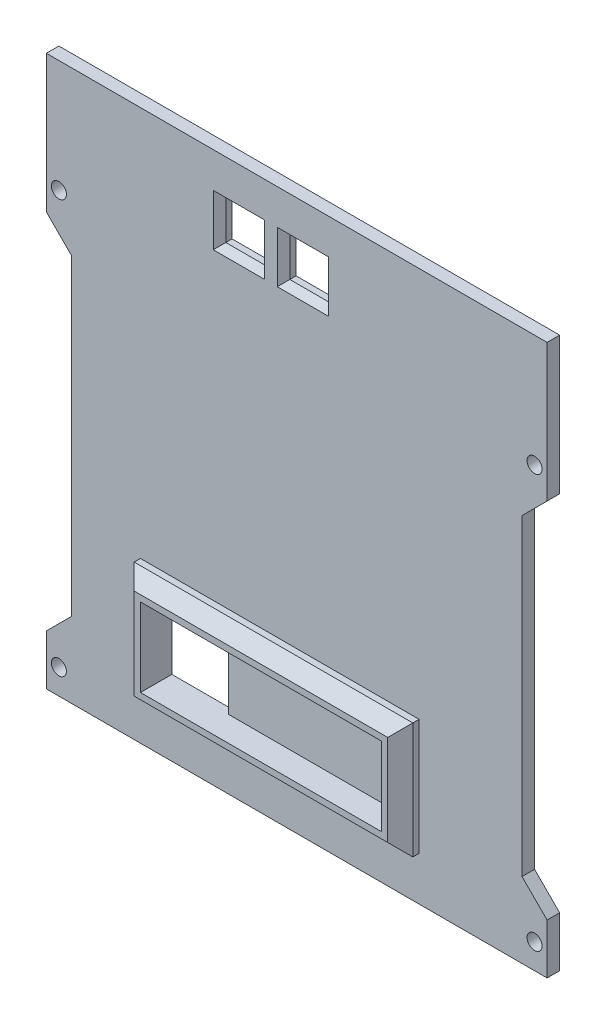
SolidWorks part; units mm, degrees
ref_plane "前视基准面" through (0, 0, 0) normal (0, 0, 1) x (1, 0, 0)
ref_plane "上视基准面" through (0, 0, 0) normal (0, 1, 0) x (1, 0, 0)
ref_plane "右视基准面" through (0, 0, 0) normal (1, 0, 0) x (0, 0, -1)
other "Configuration Table"
sketch "草图1" plane through (0, 0, 0) normal (0, 0, 1) x (1, 0, 0)
  line L0 (-68.63, 24.2) -> (-68.63, 24.3)
  line L1 (11.17, 24.2) -> (11.17, 24.3)
  line L2 (5.17, 38.1) -> (-62.63, 38.1)
  line L3 (-35.03, 25.48) -> (-40.83, 25.48) construction
  line L4 (-68.63, 24.3) -> (-62.63, 24.3)
  line L5 (-62.63, 24.3) -> (-62.63, 38.1)
  line L6 (-62.63, 38.1) -> (-68.63, 38.1)
  line L7 (-68.63, 38.1) -> (-68.63, 24.3)
  line L10 (-62.63, 38.1) -> (-68.63, 38.1)
  line L11 (-68.63, 38.1) -> (-68.63, 24.3)
  line L12 (5.17, 24.3) -> (11.17, 24.3)
  line L13 (11.17, 24.3) -> (11.17, 38.1)
  line L14 (11.17, 38.1) -> (5.17, 38.1)
  line L15 (5.17, 38.1) -> (5.17, 24.3)
  line L16 (5.17, 24.2) -> (5.17, -47.62)
  line L17 (5.17, -47.62) -> (-62.63, -47.62)
  line L18 (-62.63, -47.62) -> (-62.63, 24.2)
  line L19 (-62.63, 24.2) -> (-68.63, 24.2)
  line L20 (-68.63, 24.2) -> (-68.63, 16.2)
  line L21 (-68.63, 16.2) -> (-64.63, 12.2)
  line L22 (-64.63, 12.2) -> (-64.63, -37.62)
  line L23 (-64.63, -37.62) -> (-68.63, -41.62)
  line L24 (-68.63, -41.62) -> (-68.63, -49.62)
  line L25 (-68.63, -49.62) -> (11.17, -49.62)
  line L26 (11.17, -49.62) -> (11.17, -41.62)
  line L27 (11.17, -41.62) -> (7.17, -37.62)
  line L28 (7.17, -37.62) -> (7.17, 12.2)
  line L29 (7.17, 12.2) -> (11.17, 16.2)
  line L30 (11.17, 16.2) -> (11.17, 24.2)
  line L31 (11.17, 24.2) -> (5.17, 24.2)
  line L36 (-68.63, 24.2) -> (-68.63, 16.2)
  line L37 (-68.63, 16.2) -> (-64.63, 12.2)
  line L38 (-64.63, 12.2) -> (-64.63, -37.62)
  line L39 (-64.63, -37.62) -> (-68.63, -41.62)
  line L40 (-68.63, -41.62) -> (-68.63, -49.62)
  line L41 (-68.63, -49.62) -> (11.17, -49.62)
  line L42 (11.17, -49.62) -> (11.17, -41.62)
  line L43 (11.17, -41.62) -> (7.17, -37.62)
  line L44 (7.17, -37.62) -> (7.17, 12.2)
  line L45 (7.17, 12.2) -> (11.17, 16.2)
  line L46 (11.17, 16.2) -> (11.17, 24.2)
  line L49 (11.17, 24.3) -> (11.17, 38.1)
  line L50 (11.17, 38.1) -> (5.17, 38.1)
  line L52 (-35.03, 25.48) -> (-40.83, 25.48)
  line L53 (-35.03, 31.28) -> (-35.03, 25.48) construction
  line L54 (-35.03, 31.28) -> (-35.03, 25.48)
  line L55 (-24.83, 31.28) -> (-24.83, 25.48) construction
  line L56 (-24.83, 31.28) -> (-24.83, 25.48)
  line L57 (-24.83, 25.48) -> (-30.63, 25.48) construction
  line L58 (-24.83, 25.48) -> (-30.63, 25.48)
  line L59 (-34.83, 31.28) -> (-34.83, 25.48)
  line L60 (-40.83, 25.48) -> (-35.03, 25.48)
  line L61 (-40.83, 25.48) -> (-40.83, 31.28)
  line L62 (-40.83, 31.28) -> (-35.03, 31.28)
  line L63 (-35.03, 25.48) -> (-35.03, 31.28)
  line L64 (-30.63, 25.48) -> (-24.83, 25.48)
  line L65 (-30.63, 25.48) -> (-30.63, 31.28)
  line L66 (-30.63, 31.28) -> (-24.83, 31.28)
  line L67 (-24.83, 25.48) -> (-24.83, 31.28)
  line L68 (-35.03, 25.28) -> (-40.83, 25.28)
  line L69 (-41.03, 25.48) -> (-41.03, 31.48)
  line L70 (-41.03, 31.48) -> (-35.03, 31.48)
  line L71 (-41.03, 25.48) -> (-41.03, 25.28)
  line L72 (-41.03, 25.28) -> (-40.83, 25.28)
  line L73 (-30.83, 25.48) -> (-30.83, 31.48)
  line L74 (-41.03, 25.28) -> (-34.83, 25.28)
  line L75 (-41.03, 25.28) -> (-41.03, 31.48)
  line L76 (-41.03, 31.48) -> (-34.83, 31.48)
  line L77 (-34.83, 25.28) -> (-34.83, 31.48)
  line L78 (-30.83, 31.48) -> (-24.83, 31.48)
  line L79 (-24.63, 31.28) -> (-24.63, 25.48)
  line L81 (-30.83, 31.48) -> (-24.63, 31.48)
  line L82 (-30.83, 31.48) -> (-30.83, 25.28)
  line L83 (-30.83, 25.28) -> (-24.63, 25.28)
  line L84 (-24.63, 31.48) -> (-24.63, 25.28)
  circle A0 centre (-66.63, -45.62) radius 1.2 construction
  circle A1 centre (-66.63, -45.62) radius 1.2
  circle A2 centre (-66.63, 20.2) radius 1.2 construction
  circle A3 centre (-66.63, 20.2) radius 1.2
  circle A4 centre (9.17, 20.2) radius 1.2 construction
  circle A5 centre (9.17, 20.2) radius 1.2
  circle A6 centre (9.17, -45.62) radius 1.2 construction
  circle A7 centre (9.17, -45.62) radius 1.2
  dimension "D1" = 0
  dimension "D2" = 0
  dimension "D3" = 0
  dimension "D4" = 0.2
  dimension "D5" = 0.2
  dimension "D6" = 0.2
extrude "凸台-拉伸1" add sketch "草图1" along normal blind 2 contours L49 L50 L2 L10 L11 L0 L36 L37 L38 L39 L40 L41 L42 L43 L44 L45 L46 L1 A7 A5 A3 A1 L77 L74 L68 L72 L71 L69 L70 L76 L59 L81 L84 L79 L83 L82 L73 L78
sketch "草图2" plane through (0, 0, 2) normal (0, 0, 1) x (1, 0, 0)
  line L0 (-58.03, -22.82) -> (-39.83, -22.82) construction
  line L1 (-50.63, -27.12) -> (-12.23, -27.12)
  line L2 (-50.63, -27.12) -> (-50.63, -39.62)
  line L3 (-50.63, -39.62) -> (-12.23, -39.62)
  line L4 (-12.23, -27.12) -> (-12.23, -39.62)
  line L5 (-58.03, -22.82) -> (-39.83, -22.82)
  line L6 (-39.83, -22.82) -> (-39.83, -35.02) construction
  line L7 (-39.83, -22.82) -> (-39.83, -35.02)
  line L8 (-39.83, -35.02) -> (-39.83, -47.62) construction
  line L9 (-39.83, -35.02) -> (-39.83, -47.62)
  line L10 (-50.63, -27.12) -> (-64.63, -27.12)
  line L11 (-50.63, -39.62) -> (-50.63, -49.62)
  line L12 (11.17, 16.2) -> (11.17, 38.1)
  line L13 (11.17, 38.1) -> (-68.63, 38.1)
  line L14 (-68.63, 38.1) -> (-68.63, 16.2)
  line L15 (-68.63, 16.2) -> (-64.63, 12.2)
  line L16 (-64.63, 12.2) -> (-64.63, -37.62)
  line L17 (-64.63, -37.62) -> (-68.63, -41.62)
  line L18 (-68.63, -41.62) -> (-68.63, -49.62)
  line L19 (-68.63, -49.62) -> (11.17, -49.62)
  line L20 (11.17, -49.62) -> (11.17, -41.62)
  line L21 (11.17, -41.62) -> (7.17, -37.62)
  line L22 (7.17, -37.62) -> (7.17, 12.2)
  line L23 (7.17, 12.2) -> (11.17, 16.2)
  line L24 (11.17, 16.2) -> (11.17, 38.1)
  line L25 (11.17, 38.1) -> (-68.63, 38.1)
  line L26 (-68.63, 38.1) -> (-68.63, 16.2)
  line L27 (-68.63, 16.2) -> (-64.63, 12.2)
  line L28 (-64.63, 12.2) -> (-64.63, -37.62)
  line L29 (-64.63, -37.62) -> (-68.63, -41.62)
  line L30 (-68.63, -41.62) -> (-68.63, -49.62)
  line L31 (-68.63, -49.62) -> (11.17, -49.62)
  line L32 (11.17, -49.62) -> (11.17, -41.62)
  line L33 (11.17, -41.62) -> (7.17, -37.62)
  line L34 (7.17, -37.62) -> (7.17, 12.2)
  line L35 (7.17, 12.2) -> (11.17, 16.2)
  dimension "D2" = 38.4
  dimension "D3" = 12.5
  dimension "D4" = 14
  dimension "D5" = 10
  dimension "D1" = 0
extrude "切除-拉伸1" cut sketch "草图2" against normal blind 1 contours L7 L9 L3 L4 L1 | L9 L7 L1 L2 L3
sketch "草图3" plane through (0, 0, 1) normal (0, 0, 1) x (1, 0, 0)
  line L1 (-50.63, -27.12) -> (-40.63, -27.12)
  line L2 (-50.63, -27.12) -> (-50.63, -39.62)
  line L3 (-50.63, -39.62) -> (-40.63, -39.62)
  line L4 (-12.23, -27.12) -> (-50.63, -27.12)
  line L5 (-50.63, -27.12) -> (-50.63, -39.62)
  line L6 (-50.63, -39.62) -> (-12.23, -39.62)
  line L7 (-12.23, -39.62) -> (-12.23, -27.12)
  line L8 (-12.23, -27.12) -> (-50.63, -27.12)
  line L9 (-50.63, -27.12) -> (-50.63, -39.62)
  line L10 (-50.63, -39.62) -> (-12.23, -39.62)
  line L11 (-12.23, -39.62) -> (-12.23, -27.12)
  line L12 (-40.63, -27.12) -> (-40.63, -39.62)
  line M6 (-12.23, -27.12) -> (-50.63, -27.12)
  line M7 (-50.63, -27.12) -> (-50.63, -39.62)
  line M8 (-50.63, -39.62) -> (-12.23, -39.62)
  dimension "D2" = 10
  dimension "D1" = 0
extrude "切除-拉伸2" cut sketch "草图3" against normal blind 1 contours L12 M6 M7 M8
chamfer "倒角1" distance 1 angle 45 8 edges at (-24.63, 28.38, 2) (-27.73, 31.48, 2) (-30.83, 28.38, 2) (-27.73, 25.28, 2) (-34.83, 28.38, 2) (-37.93, 31.48, 2) (-41.03, 28.38, 2) (-37.93, 25.28, 2)
sketch "草图4" plane through (0, 0, 2) normal (0, 0, 1) x (1, 0, 0)
  line L0 (-53.63, -24.12) -> (-9.23, -24.12)
  line L1 (-9.23, -24.12) -> (-9.23, -42.62)
  line L2 (-53.63, -42.62) -> (-9.23, -42.62)
  line L3 (-53.63, -24.12) -> (-53.63, -42.62)
  line L12 (-50.63, -27.12) -> (-50.63, -39.62) construction
  line L13 (-50.63, -27.12) -> (-50.63, -39.62)
  line L14 (-50.63, -27.12) -> (-12.23, -27.12) construction
  line L15 (-50.63, -27.12) -> (-12.23, -27.12)
  line L16 (-50.63, -39.62) -> (-12.23, -39.62) construction
  line L17 (-50.63, -39.62) -> (-12.23, -39.62)
  line L18 (-12.23, -27.12) -> (-12.23, -39.62) construction
  line L19 (-12.23, -27.12) -> (-12.23, -39.62)
  line L24 (11.17, 16.2) -> (11.17, 38.1)
  line L25 (11.17, 38.1) -> (-68.63, 38.1)
  line L26 (-68.63, 38.1) -> (-68.63, 16.2)
  line L27 (-68.63, 16.2) -> (-64.63, 12.2)
  line L28 (-64.63, 12.2) -> (-64.63, -37.62)
  line L29 (-64.63, -37.62) -> (-68.63, -41.62)
  line L30 (-68.63, -41.62) -> (-68.63, -49.62)
  line L31 (-68.63, -49.62) -> (11.17, -49.62)
  line L32 (11.17, -49.62) -> (11.17, -41.62)
  line L33 (11.17, -41.62) -> (7.17, -37.62)
  line L34 (7.17, -37.62) -> (7.17, 12.2)
  line L35 (7.17, 12.2) -> (11.17, 16.2)
  line L36 (11.17, 16.2) -> (11.17, 38.1)
  line L37 (11.17, 38.1) -> (-68.63, 38.1)
  line L38 (-68.63, 38.1) -> (-68.63, 16.2)
  line L39 (-68.63, 16.2) -> (-64.63, 12.2)
  line L40 (-64.63, 12.2) -> (-64.63, -37.62)
  line L41 (-64.63, -37.62) -> (-68.63, -41.62)
  line L42 (-68.63, -41.62) -> (-68.63, -49.62)
  line L43 (-68.63, -49.62) -> (11.17, -49.62)
  line L44 (11.17, -49.62) -> (11.17, -41.62)
  line L45 (11.17, -41.62) -> (7.17, -37.62)
  line L46 (7.17, -37.62) -> (7.17, 12.2)
  line L47 (7.17, 12.2) -> (11.17, 16.2)
  line M41 (-50.63, -39.62) -> (-50.63, -27.12)
  line M42 (-50.63, -27.12) -> (-12.23, -27.12)
  line M43 (-12.23, -27.12) -> (-12.23, -39.62)
  line M44 (-12.23, -39.62) -> (-50.63, -39.62)
  dimension "D1" = 0
  dimension "D2" = 3
extrude "凸台-拉伸2" add sketch "草图4" along normal blind 3 contours L0 L3 L2 L1 M44 M41 M42 M43
chamfer "倒角2" distance 2 angle 45 4 edges at (-31.43, -24.12, 5) (-9.23, -33.37, 5) (-31.43, -42.62, 5) (-53.63, -33.37, 5)
